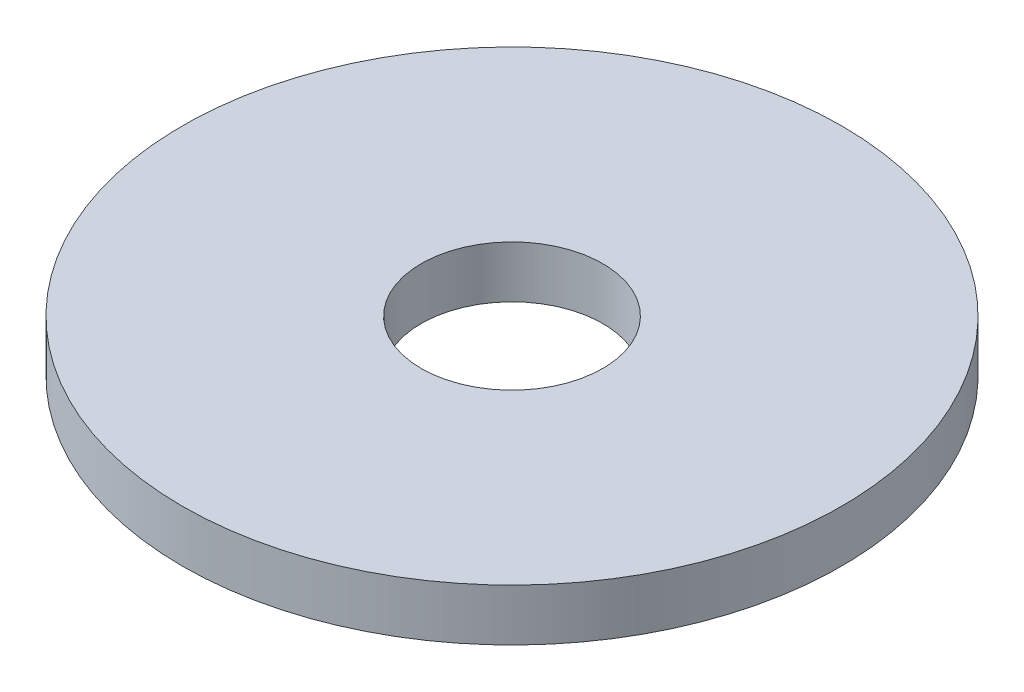
SolidWorks part; units mm, degrees
ref_plane "Front" through (0, 0, 0) normal (0, 0, 1) x (1, 0, 0)
ref_plane "Top" through (0, 0, 0) normal (0, 1, 0) x (1, 0, 0)
ref_plane "Right" through (0, 0, 0) normal (1, 0, 0) x (0, 0, -1)
sketch "Sketch1" plane through (0, 0, 0) normal (0, 1, 0) x (1, 0, 0)
  circle A0 centre (0, 0) radius 12.7
extrude "Boss-Extrude1" add sketch "Sketch1" along normal blind 2
sketch "Sketch2" plane through (0, 2, 0) normal (0, 1, 0) x (1, 0, 0)
  circle A0 centre (0, 0) radius 3.5
extrude "Cut-Extrude1" cut sketch "Sketch2" against normal blind 2
